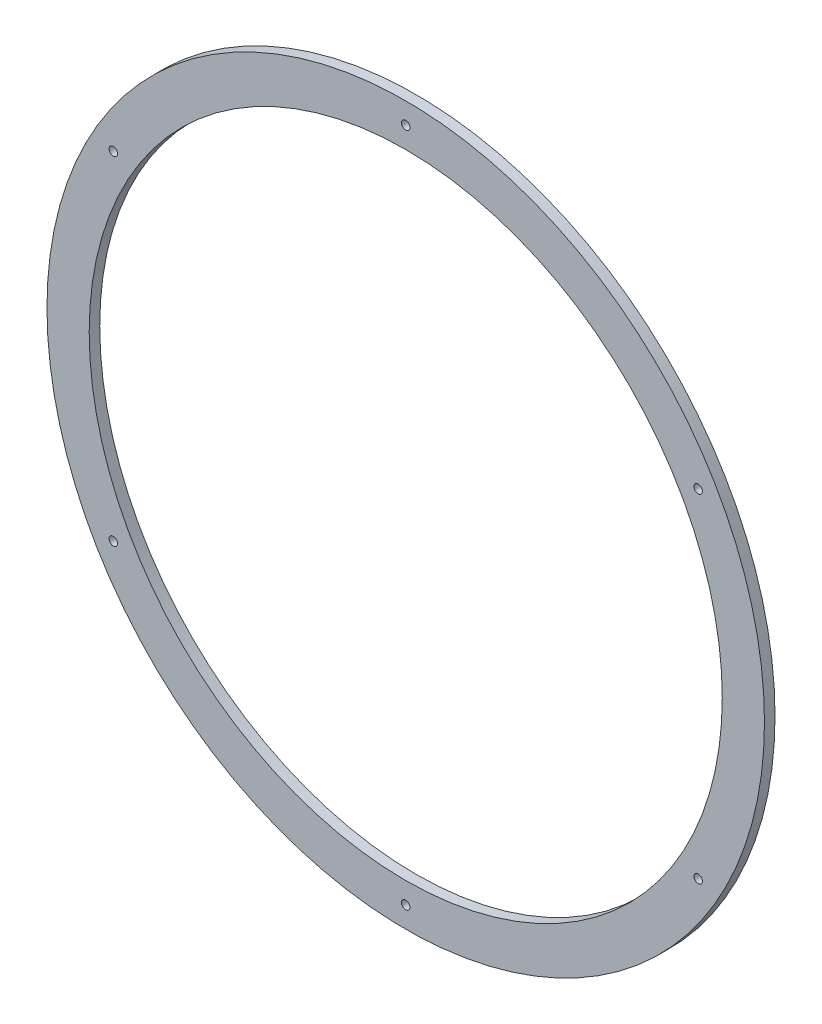
SolidWorks part; units mm, degrees
material "Plastique personnalisé"
ref_plane "Plan de face" through (0, 0, 0) normal (0, 0, 1) x (1, 0, 0)
ref_plane "Plan de dessus" through (0, 0, 0) normal (0, 1, 0) x (1, 0, 0)
ref_plane "Plan de droite" through (0, 0, 0) normal (1, 0, 0) x (0, 0, -1)
sketch "Esquisse1" plane through (0, 0, 0) normal (0, 0, 1) x (1, 0, 0)
  circle A0 centre (0, 0) radius 170
  circle A1 centre (0, 0) radius 150
  dimension "D1" = 340
  dimension "D2" = 300
extrude "Boss.-Extru.1" add sketch "Esquisse1" along normal blind 5
sketch "Esquisse2" plane through (0, 0, 5) normal (0, 0, 1) x (1, 0, 0)
  line L0 (0, 0) -> (0, 170)
  line L1 (0, 170) -> (0, 160)
  circle A0 centre (0, 0) radius 170 construction
  circle A1 centre (0, 160) radius 2
  circle A2 centre (138.5641, 80) radius 2
  circle A3 centre (138.5641, -80) radius 2
  circle A4 centre (0, -160) radius 2
  circle A5 centre (-138.5641, -80) radius 2
  circle A6 centre (-138.5641, 80) radius 2
  point P21 (0, 0)
  dimension "D2" = 4
  dimension "D1" = 10
  dimension "D3" = 6
extrude "Enlèv. mat.-Extru.1" cut sketch "Esquisse2" against normal blind 5 contours A1 | A6 | A2 | A3 | A4 | A5
